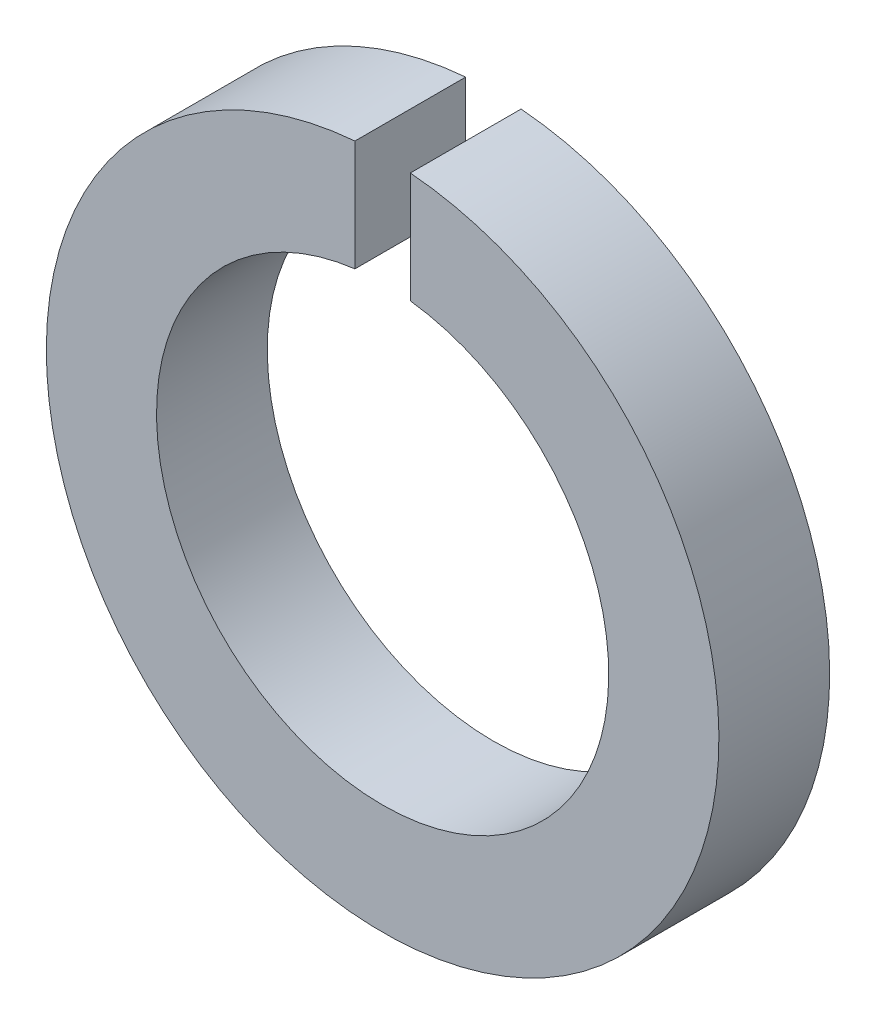
SolidWorks part; units mm, degrees
material "65Mn"
ref_plane "前视基准面" through (0, 0, 0) normal (0, 0, 1) x (1, 0, 0)
ref_plane "上视基准面" through (0, 0, 0) normal (0, 1, 0) x (1, 0, 0)
ref_plane "右视基准面" through (0, 0, 0) normal (1, 0, 0) x (0, 0, -1)
sketch "草图1" plane through (0, 0, 0) normal (0, 0, 1) x (1, 0, 0)
  line L0 (0, 0) -> (0, 103.5317) construction
  line L1 (-1.5, 18.1578) -> (-1.5, 12.1578)
  line L2 (1.5, 18.1578) -> (1.5, 12.1578)
  arc A0 (-1.5, 18.1578) -> (1.5, 18.1578) centre (0, 0) ccw
  arc A2 (-1.5, 12.1578) -> (1.5, 12.1578) centre (0, 0) ccw
  dimension "d" = 24.5
  dimension "m" = 3
  dimension "D4" = 1.5
  dimension "b" = 6
extrude "拉伸1" add sketch "草图1" along normal blind 6
equation "\"D4@草图1\" = \"m@草图1\" / 2"
